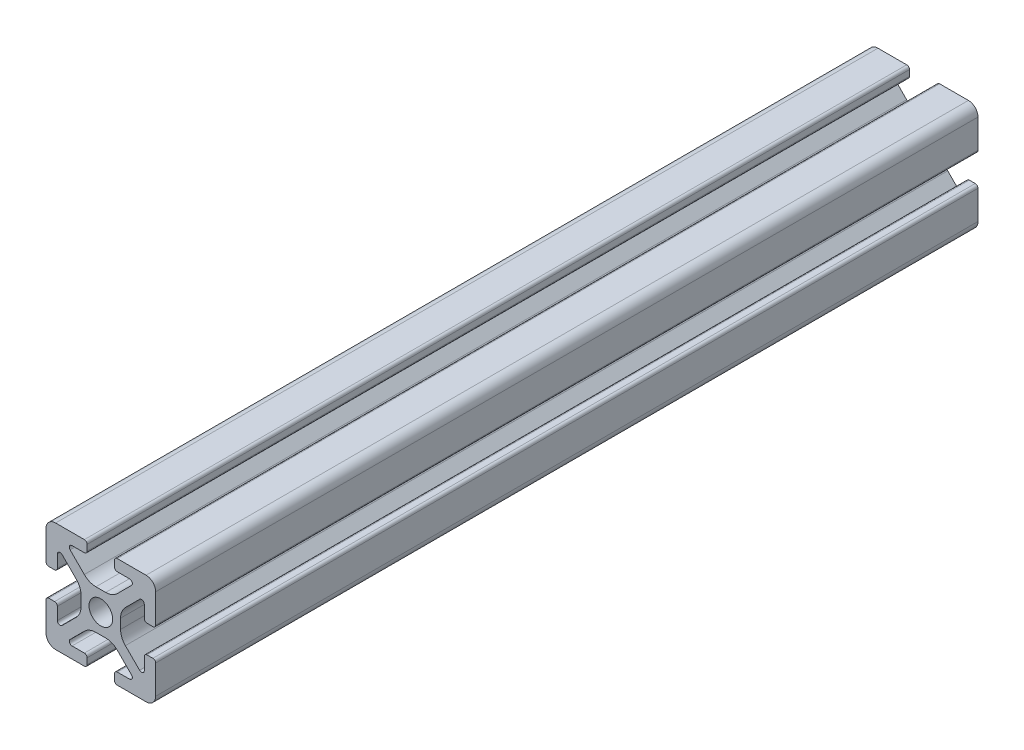
SolidWorks part; units mm, degrees
ref_plane "Front Plane" through (0, 0, 0) normal (0, 0, 1) x (1, 0, 0)
ref_plane "Top Plane" through (0, 0, 0) normal (0, 1, 0) x (1, 0, 0)
ref_plane "Right Plane" through (0, 0, 0) normal (1, 0, 0) x (0, 0, -1)
sketch "Sketch2" plane through (0, 0, 0) normal (0, 0, 1) x (1, 0, 0)
  line L0 (0, 10) -> (0, -10) construction
  line L1 (-10, 0) -> (10, 0) construction
  line L2 (2.5, -10) -> (10, -10)
  line L3 (10, -10) -> (10, -2.5)
  line L4 (2.5, -10) -> (2.5, -7.9246)
  line L5 (2.5, -7.9246) -> (6.4571, -7.9246)
  line L6 (6.4571, -7.9246) -> (2.1325, -3.6)
  line L7 (0, 0) -> (10, -10) construction
  line L8 (10, -2.5) -> (7.9246, -2.5)
  line L9 (7.9246, -2.5) -> (7.9246, -6.4571)
  line L10 (7.9246, -6.4571) -> (3.6, -2.1325)
  line L11 (5.7623, -4.2948) -> (4.2948, -5.7623) construction
  circle A0 centre (0, 0) radius 2.15
  arc A1 (5.25, -7.9246) -> (5.6036, -7.0711) centre (5.25, -7.4246) ccw construction
  point P8 (0, -3.6)
  point P16 (5.0286, -5.0286)
  dimension "Center Hole Diameter" = 4.3
  dimension "D3" = 0.5
  dimension "Rail Height" = 20
  dimension "Rail Width" = 20
  dimension "T-Slot Width" = 5
  dimension "Slot Depth" = 6.4
  dimension "Slot Inner Width" = 11.5
sketch "Sketch3" plane through (0, 0, 0) normal (1, 0, 0) x (0, 0, -1)
  line L0 (-75, -10) -> (75, -10) construction
  line L1 (-49.6, 0) -> (49.6, 0) construction
  line L2 (0, 10) -> (0, -10) construction
  line L3 (0, 10) -> (0, -10) construction
  point P6 (-49.6, 0)
  point P8 (49.6, 0)
  dimension "Length" = 150
  dimension "D1" = 25.4
sketch "Sketch4" plane through (0, 0, 0) normal (0, 0, 1) x (1, 0, 0)
  line L0 (3, -10) -> (8.25, -10)
  line L1 (2.5, -10) -> (10, -10) construction
  line L2 (2.5, -10) -> (2.5, -7.9246) construction
  line L3 (2.5, -7.9246) -> (6.4571, -7.9246) construction
  line L4 (2.5, -8.4246) -> (2.5, -9.5)
  line L5 (3, -7.9246) -> (5.25, -7.9246)
  line L6 (0, -3.6) -> (0.8898, -3.6)
  line L7 (6.4571, -7.9246) -> (2.1325, -3.6) construction
  line L8 (3.0112, -4.4787) -> (5.6036, -7.0711)
  line L9 (10, -10) -> (10, -2.5) construction
  line L10 (7.9246, -6.4571) -> (3.6, -2.1325) construction
  line L11 (7.9246, -2.5) -> (7.9246, -6.4571) construction
  line L12 (7.9246, -5.25) -> (7.9246, -3)
  line L13 (10, -2.5) -> (7.9246, -2.5) construction
  line L14 (8.4246, -2.5) -> (9.5, -2.5)
  line L15 (10, -3) -> (10, -8.25)
  line L16 (7.0711, -5.6036) -> (4.4787, -3.0112)
  line L17 (3.6, 0) -> (3.6, -0.8898)
  line L18 (-10, 0) -> (10, 0) construction
  line L19 (0, -3.6) -> (0, -2.15)
  line L20 (0, 10) -> (0, -10) construction
  line L21 (3.6, 0) -> (2.15, 0)
  arc A0 (2.5, -9.5) -> (3, -10) centre (3, -9.5) ccw
  arc A1 (5.25, -7.9246) -> (5.6036, -7.0711) centre (5.25, -7.4246) ccw construction
  arc A2 (2.5, -8.4246) -> (3, -7.9246) centre (3, -8.4246) cw
  arc A3 (5.25, -7.9246) -> (5.6036, -7.0711) centre (5.25, -7.4246) ccw
  arc A4 (0.8898, -3.6) -> (3.0112, -4.4787) centre (0.8898, -6.6) cw
  arc A5 (8.25, -10) -> (10, -8.25) centre (8.25, -8.25) ccw
  arc A6 (7.0711, -5.6036) -> (7.9246, -5.25) centre (7.4246, -5.25) ccw
  arc A7 (7.9246, -3) -> (8.4246, -2.5) centre (8.4246, -3) cw
  arc A8 (9.5, -2.5) -> (10, -3) centre (9.5, -3) cw
  arc A9 (4.4787, -3.0112) -> (3.6, -0.8898) centre (6.6, -0.8898) cw
  circle A10 centre (0, 0) radius 2.15 construction
  arc A11 (0, -2.15) -> (2.15, 0) centre (0, 0) ccw
  dimension "D1" = 1.75
  dimension "D2" = 3
extrude "Boss-Extrude1" add sketch "Sketch4" along normal mid plane 150
mirror "Mirror1" about plane through (0, 0, 0) normal (1, 0, 0) of bodies 134
mirror "Mirror2" about plane through (0, 0, 0) normal (0, 1, 0) of bodies 135
equation "\"D3@Sketch2\"=\"T-Slot Width@Sketch2\"*0.1"
equation "\"D1@Sketch4\"=\"D3@Sketch2\"*3.5"
equation "\"D2@Sketch4\"=\"D3@Sketch2\"*6"
equation "\"D1@Boss-Extrude1\"=\"Length@Sketch3\""
